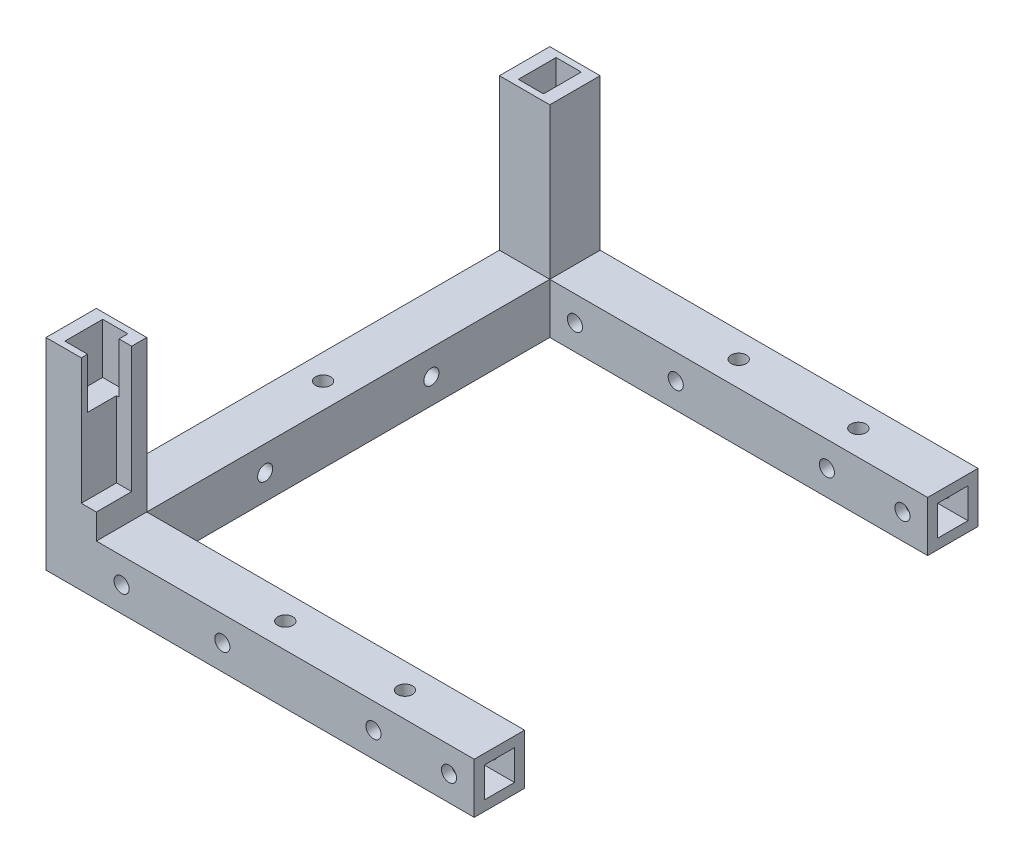
SolidWorks part; units mm, degrees
ref_plane "Front Plane" through (0, 0, 0) normal (0, 0, 1) x (1, 0, 0)
ref_plane "Top Plane" through (0, 0, 0) normal (0, 1, 0) x (1, 0, 0)
ref_plane "Right Plane" through (0, 0, 0) normal (1, 0, 0) x (0, 0, -1)
sketch "Sketch1" plane through (0, 0, 0) normal (0, 1, 0) x (1, 0, 0)
  line L0 (0, 0) -> (0, 200)
  line L1 (0, 200) -> (320, 200)
  line L2 (320, 200) -> (320, 0)
  line L3 (320, 0) -> (0, 0)
  line L4 (300, 20) -> (20, 20)
  line L5 (20, 20) -> (20, 180)
  line L6 (20, 180) -> (300, 180)
  line L7 (300, 180) -> (300, 20)
  dimension "D1" = 280
  dimension "D2" = 320
  dimension "D3" = 200
  dimension "D4" = 160
  dimension "D5" = 20
  dimension "D6" = 20
extrude "Boss-Extrude1" add sketch "Sketch1" along normal blind 20
sketch "Sketch2" plane through (0, 20, 0) normal (0, 1, 0) x (1, 0, 0)
  line L6 (320, 200) -> (0, 200) construction
  line L7 (320, 0) -> (170, 0)
  line L8 (320, 0) -> (320, 200)
  line L9 (320, 200) -> (170, 200)
  line L10 (170, 0) -> (170, 200)
  dimension "D1" = 150
extrude "Cut-Extrude1" cut sketch "Sketch2" against normal blind 20
sketch "Sketch3" plane through (0, 20, 0) normal (0, 1, 0) x (1, 0, 0)
  line L0 (0, 100) -> (195.6519, 100) construction
  line L1 (0, 0) -> (20, 0)
  line L2 (0, 0) -> (0, 20)
  line L3 (0, 20) -> (20, 20)
  line L4 (20, 0) -> (20, 20)
  line L5 (0, 200) -> (0, 0) construction
  line L6 (0, 180) -> (20, 180)
  line L7 (20, 200) -> (20, 180)
  line L8 (0, 200) -> (20, 200)
  line L9 (0, 200) -> (0, 180)
extrude "Boss-Extrude2" add sketch "Sketch3" along normal blind 60
sketch "Sketch4" plane through (0, 80, 0) normal (0, 1, 0) x (1, 0, 0)
  line L0 (0, 20) -> (0, 0) construction
  line L1 (5, 17.5) -> (15, 17.5)
  line L2 (5, 17.5) -> (5, 2.5)
  line L3 (5, 2.5) -> (15, 2.5)
  line L4 (15, 17.5) -> (15, 2.5)
  line L5 (20, 20) -> (0, 20) construction
  line L6 (20, 20) -> (20, 180) construction
  line L7 (20, 180) -> (20, 100) construction
  line L8 (20, 100) -> (87.8571, 100) construction
  line L9 (5, 197.5) -> (15, 197.5)
  line L10 (15, 182.5) -> (15, 197.5)
  line L11 (5, 182.5) -> (15, 182.5)
  line L12 (5, 182.5) -> (5, 197.5)
  dimension "D1" = 15
  dimension "D2" = 10
  dimension "D3" = 5
  dimension "D4" = 2.5
extrude "Cut-Extrude2" cut sketch "Sketch4" against normal blind 20
sketch "Sketch5" plane through (170, 0, 0) normal (1, 0, 0) x (0, 0, -1)
  line L0 (20, 0) -> (0, 0) construction
  line L1 (16, 4) -> (4, 4)
  line L2 (16, 4) -> (16, 16)
  line L3 (16, 16) -> (4, 16)
  line L4 (4, 4) -> (4, 16)
  line L5 (0, 0) -> (0, 20) construction
  line L6 (180, 0) -> (20, 0) construction
  line L7 (20, 0) -> (100, 0) construction
  line L8 (100, 0) -> (100, 76.0608) construction
  line L9 (184, 16) -> (196, 16)
  line L10 (196, 4) -> (196, 16)
  line L11 (184, 4) -> (196, 4)
  line L12 (184, 4) -> (184, 16)
  dimension "D1" = 4
  dimension "D2" = 4
  dimension "D3" = 12
  dimension "D4" = 12
extrude "Cut-Extrude3" cut sketch "Sketch5" against normal blind 22
sketch "Sketch8" plane through (0, 0, -200) normal (0, 0, -1) x (-1, 0, 0)
  line L1 (-170, 0) -> (0, 0) construction
  line L3 (0, 80) -> (0, 0) construction
  circle A0 centre (-30, 10) radius 3
  circle A1 centre (-160, 10) radius 3
  circle A2 centre (-70, 10) radius 3
  circle A3 centre (-130, 10) radius 3
  dimension "D2" = 10
  dimension "D3" = 6
  dimension "D4" = 6
  dimension "D5" = 10
  dimension "D6" = 160
  dimension "D7" = 6
  dimension "D8" = 6
  dimension "D9" = 10
  dimension "D10" = 10
  dimension "D1" = 30
  dimension "D11" = 70
  dimension "D12" = 130
extrude "Cut-Extrude5" cut sketch "Sketch8" against normal through all both and the other way through all
sketch "Sketch10" plane through (0, 0, 0) normal (0, -1, 0) x (1, 0, 0)
  line L0 (170, -20) -> (170, 0) construction
  line L1 (0, 0) -> (170, 0) construction
  line L2 (0, -100) -> (189.0588, -100) construction
  line L3 (0, -200) -> (0, 0) construction
  circle A0 centre (132.5, -10) radius 3
  circle A1 centre (85, -10) radius 3
  circle A2 centre (10, -100) radius 3
  circle A3 centre (132.5, -190) radius 3
  circle A4 centre (85, -190) radius 3
  dimension "D1" = 85
  dimension "D2" = 37.5
  dimension "D3" = 6
  dimension "D4" = 6
  dimension "D5" = 10
  dimension "D6" = 10
  dimension "D7" = 6
  dimension "D8" = 10
extrude "Cut-Extrude6" cut sketch "Sketch10" against normal blind 30
sketch "Sketch11" plane through (20, 0, 0) normal (1, 0, 0) x (0, 0, -1)
  line L1 (0, 80) -> (14, 80)
  line L2 (0, 80) -> (0, 30)
  line L3 (0, 30) -> (14, 30)
  line L4 (14, 80) -> (14, 30)
  dimension "D1" = 14
  dimension "D2" = 50
extrude "Cut-Extrude7" cut sketch "Sketch11" against normal blind 6
sketch "Sketch12" plane through (0, 0, 0) normal (-1, 0, 0) x (0, 0, 1)
  line L0 (-200, 0) -> (0, 0) construction
  line L1 (0, 80) -> (0, 0) construction
  line L2 (-200, 80) -> (-200, 0) construction
  circle A0 centre (-133, 10) radius 3
  circle A1 centre (-67, 10) radius 3
  dimension "D1" = 6
  dimension "D2" = 6
  dimension "D3" = 10
  dimension "D4" = 10
  dimension "D5" = 67
  dimension "D6" = 67
extrude "Cut-Extrude8" cut sketch "Sketch12" against normal blind 20
